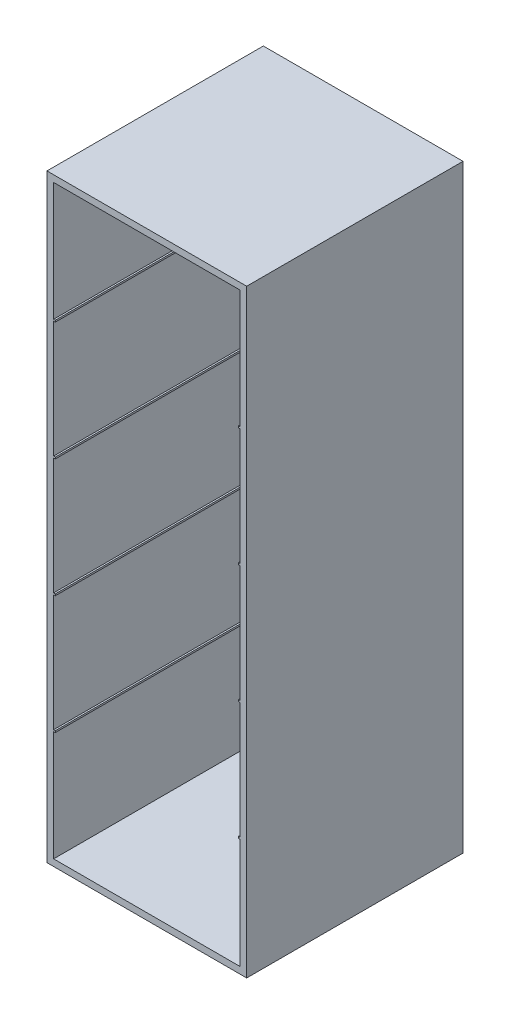
SolidWorks part; units mm, degrees
ref_plane "Front Plane" through (0, 0, 0) normal (0, 0, 1) x (1, 0, 0)
ref_plane "Top Plane" through (0, 0, 0) normal (0, 1, 0) x (1, 0, 0)
ref_plane "Right Plane" through (0, 0, 0) normal (1, 0, 0) x (0, 0, -1)
sketch "Sketch1" plane through (0, 0, 0) normal (0, 0, 1) x (1, 0, 0)
  line L1 (300, -900) -> (-300, -900)
  line L2 (300, -900) -> (300, 900)
  line L3 (300, 900) -> (-300, 900)
  line L4 (-300, -900) -> (-300, 900)
  line L5 (300, -900) -> (-300, 900) construction
  line L6 (300, 900) -> (-300, -900) construction
  point P0 (0, 0)
  dimension "D1" = 1800
  dimension "D2" = 600
extrude "Boss-Extrude1" add sketch "Sketch1" along normal blind 650
shell "Shell1" thickness 20
sketch "Sketch2" plane through (0, 0, 650) normal (0, 0, 1) x (1, 0, 0)
  line L0 (280, 880) -> (-280, 880) construction
  line L1 (0, 1176.5174) -> (0, -1168.3887) construction
  line L2 (280, 544) -> (-280, 544)
  line L3 (280, 188) -> (-280, 188)
  line L4 (280, 188) -> (280, 168)
  line L5 (280, 188) -> (-280, 188)
  line L6 (280, 544) -> (-280, 544)
  line L7 (280, 544) -> (280, 524)
  line L8 (280, 524) -> (-280, 524)
  line L9 (-280, 544) -> (-280, 524)
  line L10 (280, 524) -> (275, 524)
  line L11 (280, 524) -> (280, 519)
  line L12 (280, 519) -> (275, 519)
  line L13 (275, 524) -> (275, 519)
  line L14 (-280, 524) -> (-275, 524)
  line L15 (-280, 524) -> (-280, 519)
  line L16 (-280, 519) -> (-275, 519)
  line L17 (-275, 524) -> (-275, 519)
  line L18 (280, -880) -> (280, 880) construction
  line L19 (-280, 880) -> (-280, -880) construction
  line L20 (280, 168) -> (-280, 168)
  line L21 (-280, 188) -> (-280, 168)
  line L22 (280, 168) -> (275, 168)
  line L23 (280, 168) -> (280, 163)
  line L24 (280, 163) -> (275, 163)
  line L25 (275, 168) -> (275, 163)
  line L26 (280, -168) -> (-280, -168)
  line L27 (280, -524) -> (-280, -524)
  line L28 (280, -168) -> (-280, -168)
  line L29 (280, -168) -> (280, -188)
  line L30 (280, -188) -> (-280, -188)
  line L31 (-280, -168) -> (-280, -188)
  line L32 (280, -188) -> (275, -188)
  line L33 (280, -188) -> (280, -193)
  line L34 (280, -193) -> (275, -193)
  line L35 (275, -188) -> (275, -193)
  line L37 (280, -524) -> (-280, -524)
  line L38 (280, -524) -> (280, -544)
  line L39 (280, -544) -> (-280, -544)
  line L40 (-280, -524) -> (-280, -544)
  line L41 (280, -544) -> (275, -544)
  line L42 (280, -544) -> (280, -549)
  line L43 (280, -549) -> (275, -549)
  line L44 (275, -544) -> (275, -549)
  line M24 (280, 880) -> (280, -880)
  dimension "D1" = 336
  dimension "D2" = 20
  dimension "D3" = 5
  dimension "D4" = 336
  dimension "D5" = 20
  dimension "D6" = 5
  dimension "D7" = 5
  dimension "D8" = 336
  dimension "D9" = 20
  dimension "D10" = 5
  dimension "D11" = 5
  dimension "D12" = 336
  dimension "D13" = 20
  dimension "D14" = 5
  dimension "D15" = 5
extrude "Boss-Extrude2" add sketch "Sketch2" against normal up to next contours L8 L13 L12 M24 | L20 L25 L24 M24 | L30 L35 L34 M24 | L39 L44 L43 M24
sketch "Sketch3" plane through (0, 0, 650) normal (0, 0, 1) x (1, 0, 0)
  line L0 (0, 1173.1856) -> (0, -1169.2047) construction
mirror "Mirror1" about plane through (0, 0, 0) normal (1, 0, 0) of "Boss-Extrude2"
